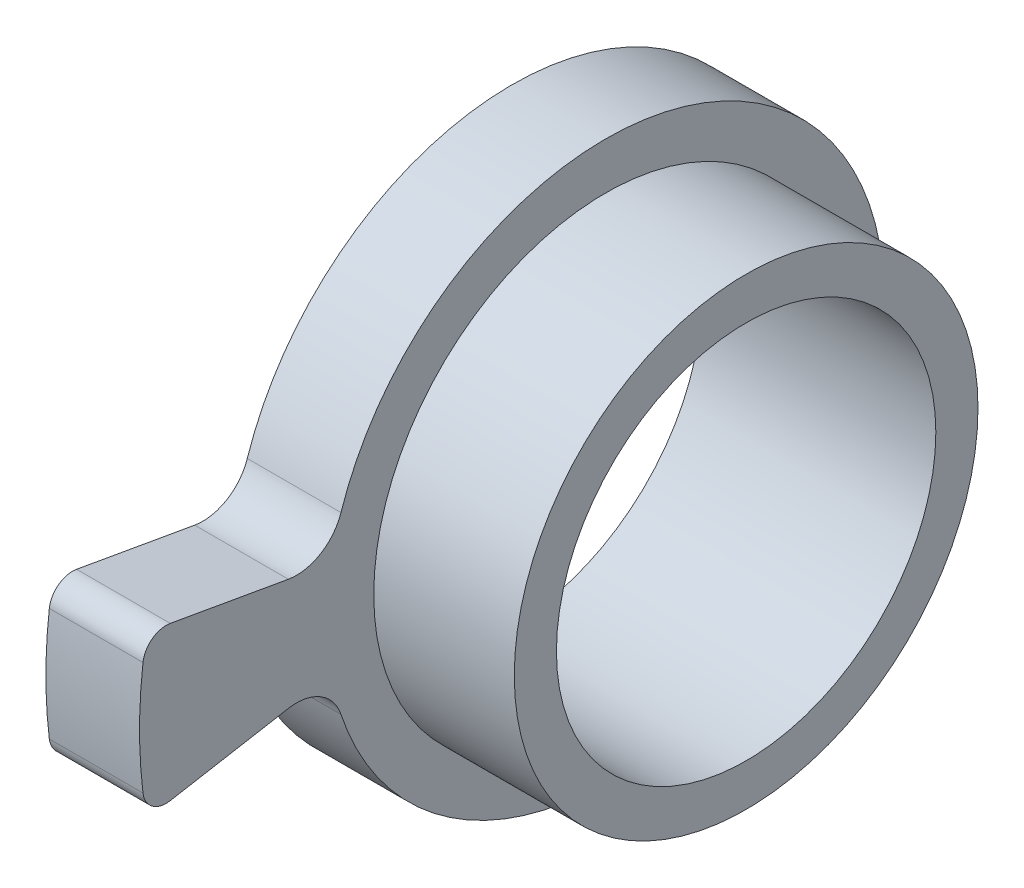
SolidWorks part; units mm, degrees
ref_plane "Plan de face" through (0, 0, 0) normal (0, 0, 1) x (1, 0, 0)
ref_plane "Plan de dessus" through (0, 0, 0) normal (0, 1, 0) x (1, 0, 0)
ref_plane "Plan de droite" through (0, 0, 0) normal (1, 0, 0) x (0, 0, -1)
sketch "Esquisse1" plane through (0, 0, 0) normal (0, 0, 1) x (1, 0, 0)
  line L0 (-3.996, 0) -> (6.4349, 0) construction
  line L1 (0, 4.05) -> (0, 5.95)
  line L2 (0, 5.95) -> (2, 5.95)
  line L3 (2, 5.95) -> (2, 4.95)
  line L4 (2, 4.95) -> (5, 4.95)
  line L5 (5, 4.95) -> (5, 4.05)
  line L6 (5, 4.05) -> (0, 4.05)
  dimension "D1" = 8.1
  dimension "D2" = 9.9
  dimension "D3" = 1
  dimension "D4" = 2
  dimension "D5" = 3
revolve "Révolution1" add sketch "Esquisse1" angle 360 about L0
sketch "Esquisse2" plane through (0, 0, 0) normal (-1, 0, 0) x (0, 0, 1)
  line L0 (5.8596, -1.0332) -> (9.7988, -1.7278)
  line L4 (5.8596, 1.0332) -> (9.7988, 1.7278)
  circle A4 centre (0, 0) radius 5.95 construction
  circle A5 centre (0, 0) radius 9.95
  arc A6 (9.7988, -1.7278) -> (9.7988, 1.7278) centre (0, 0) ccw
  arc A9 (5.8596, -1.0332) -> (5.8596, 1.0332) centre (0, 0) ccw
  point P0 (0, 0.1606)
  point P7 (-0.1797, 0)
  dimension "D1" = 20
  dimension "D2" = 4
extrude "Boss.-Extru.1" add sketch "Esquisse2" against normal up to surface (2 mm away) up to face at (2, 0, 5.95)
fillet "Congé1" radius 1 2 edges at (1, -1.0332, 5.8596) (1, 1.0332, 5.8596)
fillet "Congé3" radius 0.5 2 edges at (1, 1.7278, 9.7988) (1, -1.7278, 9.7988)
